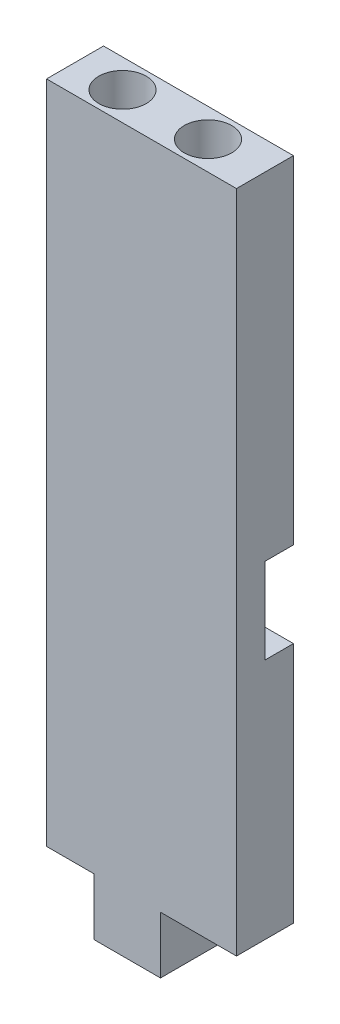
SolidWorks part; units mm, degrees
material "Plywood"
ref_plane "Plan de face" through (0, 0, 0) normal (0, 0, 1) x (1, 0, 0)
ref_plane "Plan de dessus" through (0, 0, 0) normal (0, 1, 0) x (1, 0, 0)
ref_plane "Plan de droite" through (0, 0, 0) normal (1, 0, 0) x (0, 0, -1)
sketch "Esquisse1" plane through (0, 0, 0) normal (0, 0, 1) x (1, 0, 0)
  line L1 (0, 0) -> (20, 0)
  line L2 (0, 0) -> (0, 70)
  line L3 (0, 70) -> (20, 70)
  line L4 (20, 0) -> (20, 70)
  dimension "D1" = 20
  dimension "D2" = 70
extrude "Boss.-Extru.1" add sketch "Esquisse1" along normal blind 6
sketch "Esquisse2" plane through (0, 0, 0) normal (0, 0, -1) x (-1, 0, 0)
  line L0 (0, 70) -> (0, 0) construction
  line L1 (0, 25.5) -> (-8, 25.5)
  line L2 (0, 25.5) -> (0, 34.5)
  line L3 (0, 34.5) -> (-8, 34.5)
  line L4 (-8, 25.5) -> (-8, 34.5)
  line L5 (-20, 0) -> (-20, 70) construction
  line L6 (-20, 25.5) -> (-13, 25.5)
  line L7 (-20, 25.5) -> (-20, 34.5)
  line L8 (-20, 34.5) -> (-13, 34.5)
  line L9 (-13, 25.5) -> (-13, 34.5)
  line L10 (-8, 25.5) -> (2, 25.5) construction
  line L11 (-8, 34.5) -> (2, 34.5) construction
  line L12 (-13, 34.5) -> (-13, 25.5) construction
  line L13 (-8, 34.5) -> (-8, 25.5) construction
extrude "Enlèv. mat.-Extru.1" cut sketch "Esquisse2" against normal blind 3
sketch "Esquisse3" plane through (0, 0, 0) normal (0, -1, 0) x (1, 0, 0)
  line L0 (0, 0) -> (20, 0) construction
  line L1 (12, 0) -> (5, 0)
  line L2 (12, 0) -> (12, 6)
  line L3 (12, 6) -> (5, 6)
  line L4 (5, 0) -> (5, 6)
  line L5 (0, 6) -> (20, 6) construction
extrude "Boss.-Extru.2" add sketch "Esquisse3" along normal blind 6
sketch "Esquisse4" plane through (0, 70, 0) normal (0, 1, 0) x (1, 0, 0)
  line L0 (20, 0) -> (0, 0) construction
  line L1 (0, -6) -> (0, 0) construction
  circle A0 centre (5, -3) radius 2.5
  dimension "D1" = 5
  dimension "D2" = 3
  dimension "D3" = 5
extrude "Enlèv. mat.-Extru.2" cut sketch "Esquisse4" against normal blind 10
pattern_linear "Répétition linéaire1" count 2 spacing 9 along (1, 0, 0) of "Enlèv. mat.-Extru.2"
